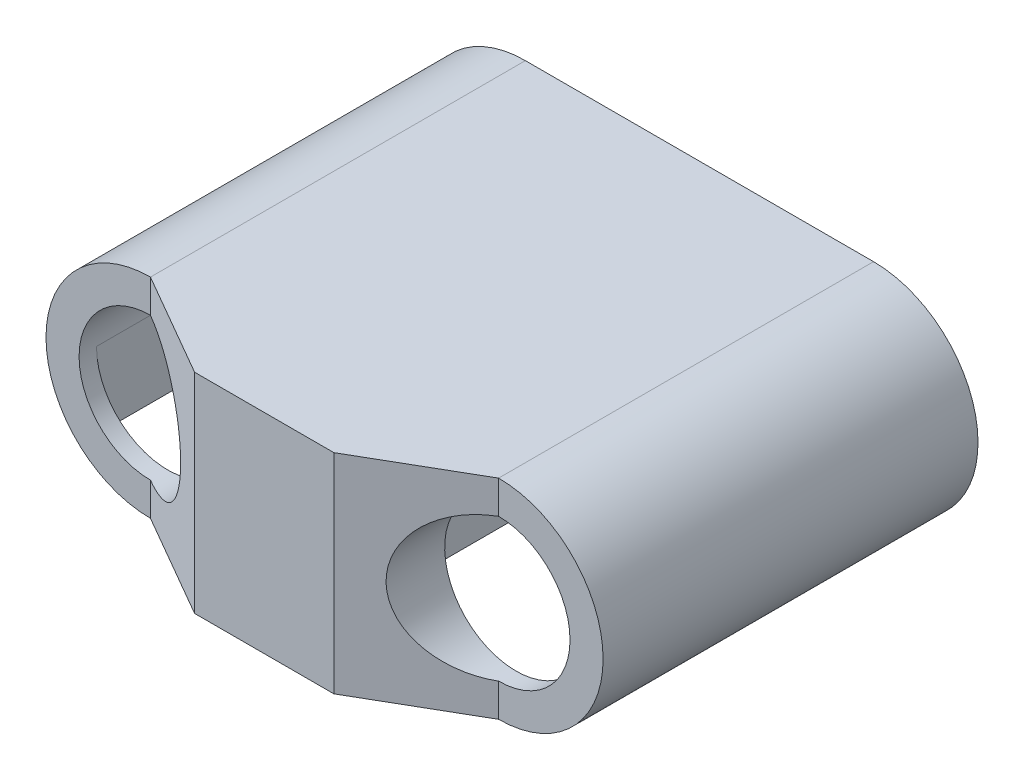
SolidWorks part; units mm, degrees
ref_plane "Front Plane" through (0, 0, 0) normal (0, 0, 1) x (1, 0, 0)
ref_plane "Top Plane" through (0, 0, 0) normal (0, 1, 0) x (1, 0, 0)
ref_plane "Right Plane" through (0, 0, 0) normal (1, 0, 0) x (0, 0, -1)
sketch "Sketch1" plane through (0, 0, 0) normal (0, 0, 1) x (1, 0, 0)
  line L0 (-100, 0) -> (100, 0) construction
  line L1 (0, 0) -> (0, 50) construction
  line L2 (-100, 0) -> (100, 0) construction
  line L3 (-100, 60) -> (100, 60)
  line L4 (-100, -60) -> (100, -60)
  circle A0 centre (100, 0) radius 41
  circle A1 centre (-100, 0) radius 41
  circle A2 centre (100, 0) radius 49 construction
  circle A3 centre (-100, 0) radius 49 construction
  arc A4 (-100, 60) -> (-100, -60) centre (-100, 0) ccw
  arc A5 (100, -60) -> (100, 60) centre (100, 0) ccw
  point P9 (0, 0)
  dimension "D1" = 82
  dimension "D4" = 98
  dimension "D5" = 60
  dimension "D2" = 100
  dimension "D3" = 50
extrude "Boss-Extrude1" add sketch "Sketch1" along normal blind 250
sketch "Sketch4" plane through (0, 0, 0) normal (0, 0, 1) x (1, 0, 0)
  line L1 (-100, -55) -> (100, -55)
  line L6 (-100, 55) -> (-100, 75)
  line L7 (-100, 75) -> (100, 75)
  line L8 (100, 75) -> (100, 55)
  arc A0 (-100, 55) -> (-100, -55) centre (-100, 0) ccw
  arc A1 (100, -55) -> (100, 55) centre (100, 0) ccw
  dimension "D1" = 55
  dimension "D4" = 55
  dimension "D2" = 100
  dimension "D3" = 100
  dimension "D5" = 200
  dimension "D6" = 100
  dimension "D7" = 100
  dimension "D8" = 20
  dimension "D9" = 200
sketch "Sketch5" plane through (0, 0, 0) normal (0, 1, 0) x (1, 0, 0)
  line L1 (100, -250) -> (-100, -250) construction
  line L3 (40, -250) -> (-40, -250)
  line L4 (-40, -250) -> (-100, -215.359)
  line L5 (-100, -250) -> (-100, 0) construction
  line L6 (-100, -215.359) -> (-160, -215.359)
  line L7 (-160, -215.359) -> (-160, -312.3312)
  line L8 (-160, -312.3312) -> (8.3267, -312.3312)
  line L9 (-160, 0) -> (-160, -250) construction
  line L12 (160, -312.3312) -> (-8.3267, -312.3312)
  line L13 (160, -215.359) -> (160, -312.3312)
  line L14 (100, -215.359) -> (160, -215.359)
  line L15 (40, -250) -> (100, -215.359)
  dimension "D2" = 30
extrude "Cut-Extrude2" cut sketch "Sketch5" against normal mid plane 260 contours L15 L3 L4 L6 L7 L8 L12 L13 L14
sketch "Sketch6" plane through (0, 0, 0) normal (0, 1, 0) x (1, 0, 0)
  line L0 (0, -250) -> (0, 0) construction
  line L1 (40, -250) -> (-40, -250) construction
  line L2 (100, 0) -> (-100, 0) construction
  line L3 (160, -173.3468) -> (36.3203, -173.3468)
  line L4 (160, -215.359) -> (160, 0) construction
  line L5 (36.3203, -173.3468) -> (25.094, -162.1206)
sketch "Sketch7" plane through (0, 0, 0) normal (0, 0, -1) x (-1, 0, 0)
  line L0 (-100, 41) -> (-5, 41) construction
  line L1 (0, 41) -> (0, 0) construction
  line L2 (100, 41) -> (5, 41)
  line L3 (141, 0) -> (141, -85.7279)
  line L4 (-141, 0) -> (-141, -85.7279)
  line L5 (-141, -85.7279) -> (-5, -85.7279)
  line L6 (-5, 41) -> (-5, -85.7279)
  line L7 (5, 41) -> (5, -85.7279)
  line L8 (5, 41) -> (100, 41) construction
  line L9 (-5, 41) -> (-100, 41)
  line L10 (5, -85.7279) -> (141, -85.7279)
  circle A0 centre (-100, 0) radius 41 construction
  arc A1 (-100, 41) -> (-141, 0) centre (-100, 0) ccw
  arc A2 (100, 41) -> (141, 0) centre (100, 0) cw
  point P14 (0, -85.7279)
  dimension "D1" = 5
extrude "Cut-Extrude3" cut sketch "Sketch7" against normal offset from surface (205.359 mm away) 10 up to face at (125.25, 0, 215.359)
fillet "Fillet1" radius 5 4 edges at (5, -9.5, 205.359) (5, 41, 102.6795) (-5, 41, 102.6795) (-5, -9.5, 205.359)
